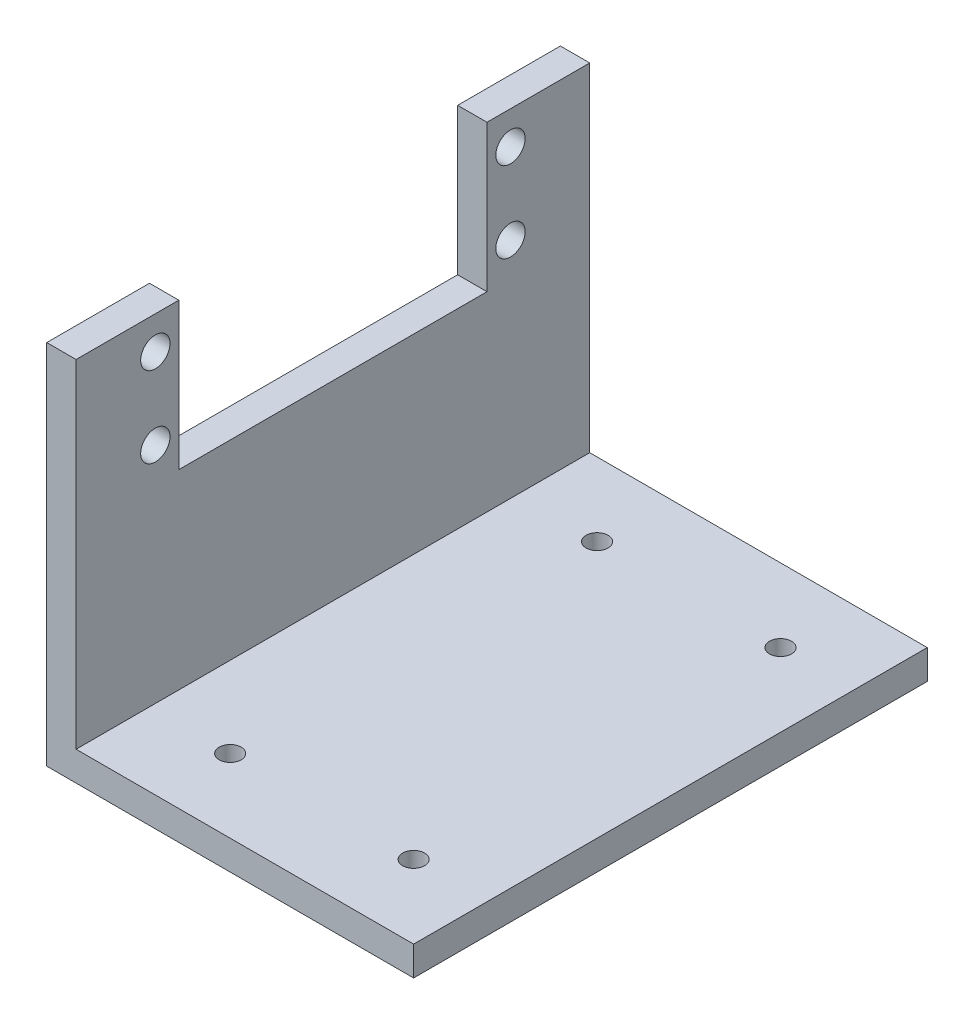
SolidWorks part; units mm, degrees
ref_plane "Plan de face" through (0, 0, 0) normal (0, 0, 1) x (1, 0, 0)
ref_plane "Plan de dessus" through (0, 0, 0) normal (0, 1, 0) x (1, 0, 0)
ref_plane "Plan de droite" through (0, 0, 0) normal (1, 0, 0) x (0, 0, -1)
sketch "Esquisse1" plane through (0, 0, 0) normal (0, 0, 1) x (1, 0, 0)
  line L1 (0, 0) -> (4, 0)
  line L2 (0, 0) -> (0, 50)
  line L3 (0, 50) -> (4, 50)
  line L4 (4, 4) -> (4, 50)
  line L5 (4, 0) -> (50, 0)
  line L7 (4, 4) -> (50, 4)
  line L8 (50, 0) -> (50, 4)
  dimension "D1" = 4
  dimension "D2" = 4
  dimension "D3" = 50
  dimension "D4" = 46
  dimension "D5" = 4
extrude "Extrusion1" add sketch "Esquisse1" along normal blind 70
sketch "Esquisse2" plane through (0, 0, 0) normal (-1, 0, 0) x (0, 0, 1)
  line L0 (14, 50) -> (56, 50)
  line L1 (14, 50) -> (14, 30)
  line L2 (56, 50) -> (56, 30)
  line L3 (14, 30) -> (56, 30)
  line L4 (70, 50) -> (0, 50) construction
  line L5 (0, 50) -> (0, 0) construction
  dimension "D1" = 42
  dimension "D2" = 20
  dimension "D3" = 14
extrude "Extrusion2" cut sketch "Esquisse2" against normal blind 70
sketch "Esquisse4" plane through (0, 4, 0) normal (0, 1, 0) x (1, 0, 0)
  line L0 (50, -70) -> (4, -70) construction
  line L1 (50, -70) -> (50, 0) construction
  circle A0 centre (40, -60) radius 1.5
  dimension "D1" = 3
  dimension "D2" = 10
  dimension "D3" = 10
extrude "Extrusion3" cut sketch "Esquisse4" against normal through all
pattern_linear "Répétition linéaire1" count 2 spacing 50 along (0, 0, -1) count 2 spacing 25 along (-1, 0, 0) of "Extrusion3"
sketch "Esquisse5" plane through (0, 0, 0) normal (-1, 0, 0) x (0, 0, 1)
  circle A0 centre (59.2, 45.5) radius 2
extrude "Enlèv. mat.-Extru.1" cut sketch "Esquisse5" against normal blind 10
sketch "Esquisse6" plane through (0, 0, 0) normal (-1, 0, 0) x (0, 0, 1)
  circle A0 centre (59.2, 34.5) radius 2
extrude "Enlèv. mat.-Extru.2" cut sketch "Esquisse6" against normal blind 10
sketch "Esquisse7" plane through (0, 0, 0) normal (-1, 0, 0) x (0, 0, 1)
  circle A0 centre (10.8, 34.5) radius 2
extrude "Enlèv. mat.-Extru.3" cut sketch "Esquisse7" against normal blind 10
sketch "Esquisse8" plane through (0, 0, 0) normal (-1, 0, 0) x (0, 0, 1)
  circle A0 centre (10.8, 45.5) radius 2
extrude "Enlèv. mat.-Extru.4" cut sketch "Esquisse8" against normal blind 10
